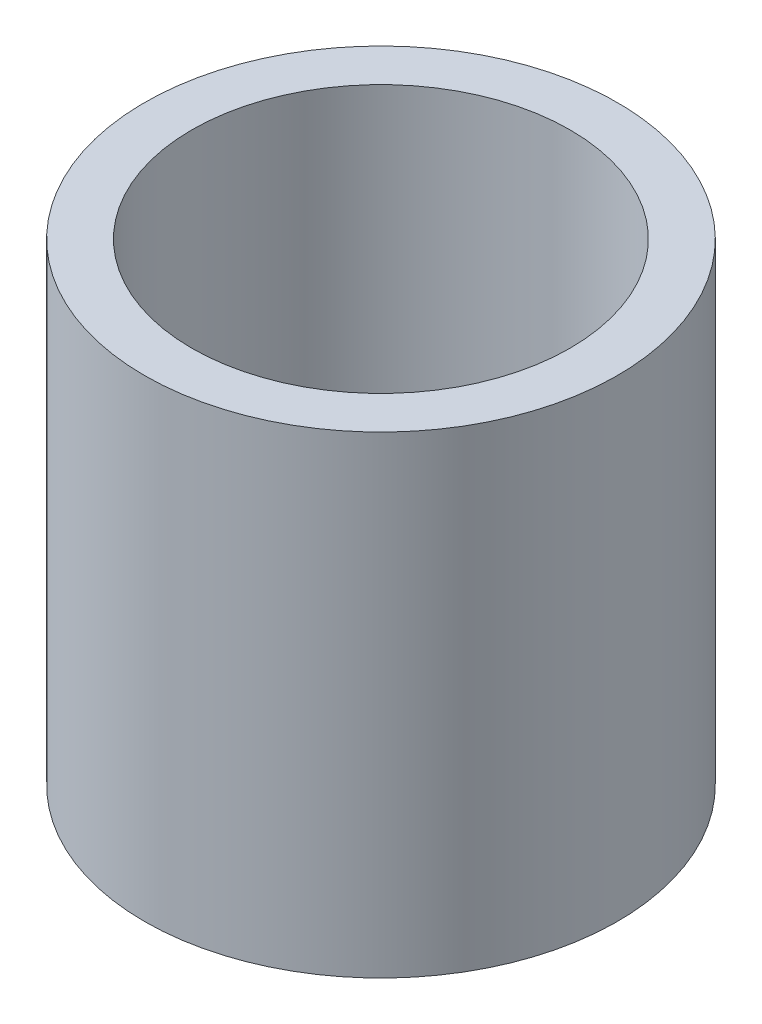
SolidWorks part; units mm, degrees
ref_plane "Front Plane" through (0, 0, 0) normal (0, 0, 1) x (1, 0, 0)
ref_plane "Top Plane" through (0, 0, 0) normal (0, 1, 0) x (1, 0, 0)
ref_plane "Right Plane" through (0, 0, 0) normal (1, 0, 0) x (0, 0, -1)
sketch "Sketch1" plane through (0, 0, 0) normal (0, 1, 0) x (1, 0, 0)
  circle A0 centre (0, 0) radius 4
  circle A1 centre (0, 0) radius 5
  dimension "D1" = 10
  dimension "D2" = 8
extrude "Boss-Extrude1" add sketch "Sketch1" along normal blind 10
